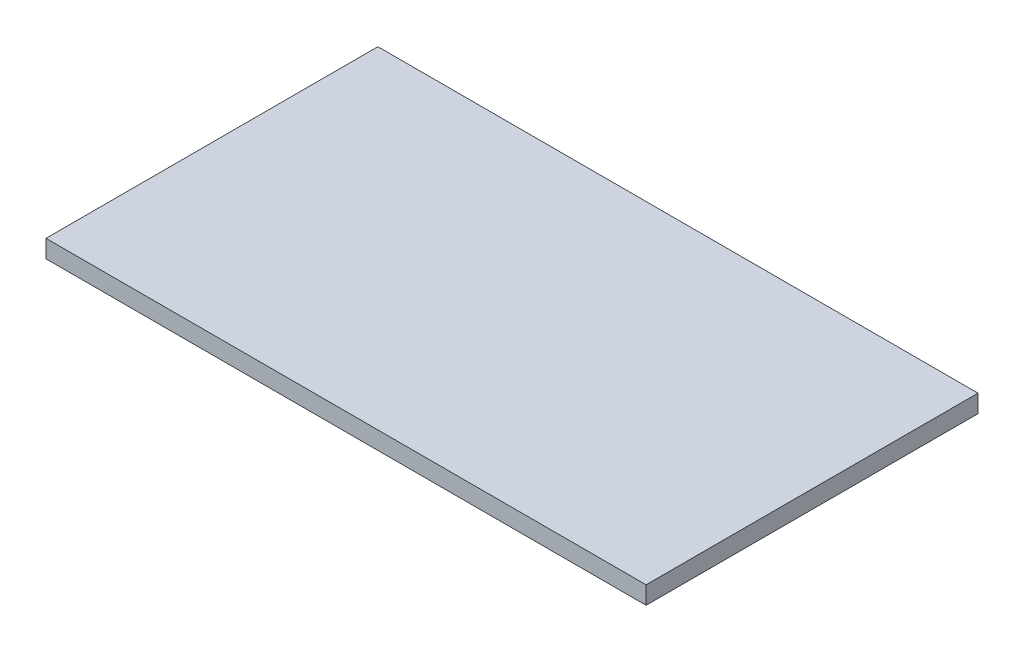
SolidWorks part; units mm, degrees
ref_plane "Front Plane" through (0, 0, 0) normal (0, 0, 1) x (1, 0, 0)
ref_plane "Top Plane" through (0, 0, 0) normal (0, 1, 0) x (1, 0, 0)
ref_plane "Right Plane" through (0, 0, 0) normal (1, 0, 0) x (0, 0, -1)
sketch "Sketch1" plane through (0, 0, 0) normal (0, 1, 0) x (1, 0, 0)
  line L1 (321.4687, 177.8) -> (-321.4688, 177.8)
  line L2 (321.4687, 177.8) -> (321.4687, -177.8)
  line L3 (321.4687, -177.8) -> (-321.4687, -177.8)
  line L4 (-321.4688, 177.8) -> (-321.4687, -177.8)
  line L5 (321.4687, 177.8) -> (-321.4687, -177.8) construction
  line L6 (321.4687, -177.8) -> (-321.4688, 177.8) construction
  point P0 (0, 0)
  dimension "D1" = 642.9375
  dimension "D2" = 355.6
extrude "Boss-Extrude1" add sketch "Sketch1" along normal blind 19.05
